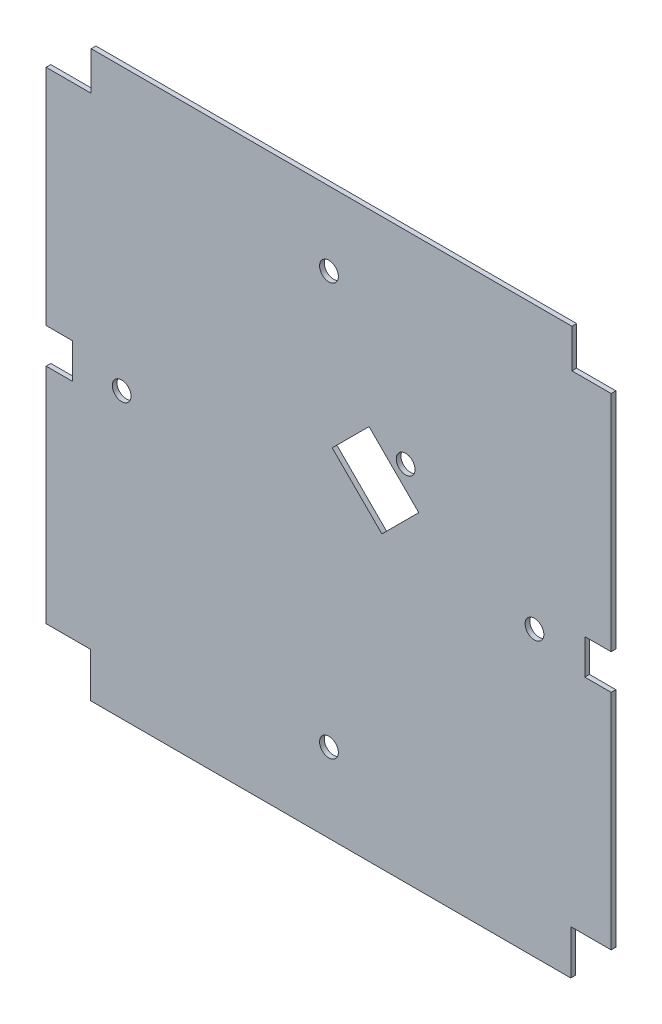
SolidWorks part; units mm, degrees
ref_plane "Front Plane" through (0, 0, 0) normal (0, 0, 1) x (1, 0, 0)
ref_plane "Top Plane" through (0, 0, 0) normal (0, 1, 0) x (1, 0, 0)
ref_plane "Right Plane" through (0, 0, 0) normal (1, 0, 0) x (0, 0, -1)
sketch "Sketch1" plane through (0, 0, 0) normal (0, 0, 1) x (1, 0, 0)
  line L1 (-67.0247, 35.727) -> (29.4753, 35.727)
  line L2 (-67.0247, 35.727) -> (-67.0247, -60.773)
  line L3 (-67.0247, -60.773) -> (29.4753, -60.773)
  line L4 (29.4753, 35.727) -> (29.4753, -60.773)
  line L5 (-67.0247, 35.727) -> (-59.3247, 35.727)
  line L6 (-67.0247, 35.727) -> (-67.0247, 29.127)
  line L7 (-67.0247, 29.127) -> (-59.3247, 29.127)
  line L8 (-59.3247, 35.727) -> (-59.3247, 29.127)
  line L21 (-67.0247, -9.073) -> (-62.5247, -9.073)
  line L22 (-67.0247, -9.073) -> (-67.0247, -15.073)
  line L23 (-67.0247, -15.073) -> (-62.5247, -15.073)
  line L24 (-62.5247, -9.073) -> (-62.5247, -15.073)
  line L25 (29.4753, 35.727) -> (22.7753, 35.727)
  line L26 (29.4753, 35.727) -> (29.4753, 29.127)
  line L27 (29.4753, 29.127) -> (22.7753, 29.127)
  line L28 (22.7753, 35.727) -> (22.7753, 29.127)
  line L29 (29.4753, -15.073) -> (24.9753, -15.073)
  line L30 (29.4753, -15.073) -> (29.4753, -9.073)
  line L31 (29.4753, -9.073) -> (24.9753, -9.073)
  line L32 (24.9753, -15.073) -> (24.9753, -9.073)
  line L33 (29.4753, -60.773) -> (22.5753, -60.773)
  line L34 (29.4753, -60.773) -> (29.4753, -53.173)
  line L35 (29.4753, -53.173) -> (22.5753, -53.173)
  line L36 (22.5753, -60.773) -> (22.5753, -53.173)
  line L37 (-67.0247, -60.773) -> (-59.4247, -60.773)
  line L38 (-67.0247, -60.773) -> (-67.0247, -53.173)
  line L39 (-67.0247, -53.173) -> (-59.4247, -53.173)
  line L40 (-59.4247, -60.773) -> (-59.4247, -53.173)
  circle A0 centre (-18.7247, 23.127) radius 1.6
  circle A1 centre (-54.1247, -12.273) radius 1.6
  circle A2 centre (16.3753, -12.273) radius 1.6
  circle A3 centre (-18.7247, -47.273) radius 1.6
  circle A4 centre (-5.6247, 1.127) radius 1.6
  point P38 (0, 0)
  point P44 (3.9082, 1.6491)
  dimension "D17" = 3.2
  dimension "D19" = 3.2
  dimension "D20" = 3.2
  dimension "D21" = 3.2
  dimension "D27" = 3.2
  dimension "D1" = 96.5
  dimension "D2" = 96.5
  dimension "D3" = 4.5
  dimension "D4" = 7.7
  dimension "D5" = 6.6
  dimension "D6" = 6
  dimension "D7" = 45.7
  dimension "D8" = 7.6
  dimension "D9" = 7.6
  dimension "D10" = 6.9
  dimension "D11" = 7.6
  dimension "D12" = 6
  dimension "D13" = 4.5
  dimension "D14" = 6.6
  dimension "D15" = 6.7
  dimension "D16" = 12.9
  dimension "D18" = 48.3
  dimension "D22" = 13.5
  dimension "D23" = 48.5
  dimension "D24" = 0
  dimension "D25" = 83.9
  dimension "D26" = 83.4
  dimension "D31" = 61.9
  dimension "D32" = 61.4
extrude "Boss-Extrude1" add sketch "Sketch1" along normal blind 0.8 contours L40 L3 L36 L35 L4 L29 L32 L31 L27 L28 L1 L8 L7 L2 L21 L24 L23 L39 A4 A3 A2 A1 A0
sketch "Sketch2" plane through (0, 0, 0.8) normal (0, 0, 1) x (1, 0, 0)
  line L0 (-11.8759, 3.5611) -> (-3.3906, -4.9242)
  line L1 (-11.8759, 3.5611) -> (-18.1691, -2.7321)
  line L2 (-3.3906, -4.9242) -> (-9.6838, -11.2174)
  line L3 (-18.1691, -2.7321) -> (-9.6838, -11.2174)
  line L4 (-16.4169, -0.98) -> (-7.9317, -9.4652)
  line L5 (-5.0325, -6.5661) -> (-13.5178, 1.9192)
  line L6 (-59.4247, -60.773) -> (22.5753, -60.773) construction
  line L7 (-67.0247, -15.073) -> (-67.0247, -53.173) construction
  point P10 (-10.7247, -3.773)
  dimension "D1" = 45
  dimension "D2" = 8.9
  dimension "D3" = 12
  dimension "D4" = 4.1
  dimension "D5" = 2.05
  dimension "D6" = 6
  dimension "D7" = 56.3
  dimension "D8" = 57
extrude "Cut-Extrude1" cut sketch "Sketch2" against normal blind 0.8 contours L4 L1 L3 L2 | L2 L5 L1 L4 | L5 L2 L0 L1
equation "\"D5@Sketch2\"=\"D4@Sketch2\"/2"
equation "\"D6@Sketch2\"=\"D3@Sketch2\"/2"
